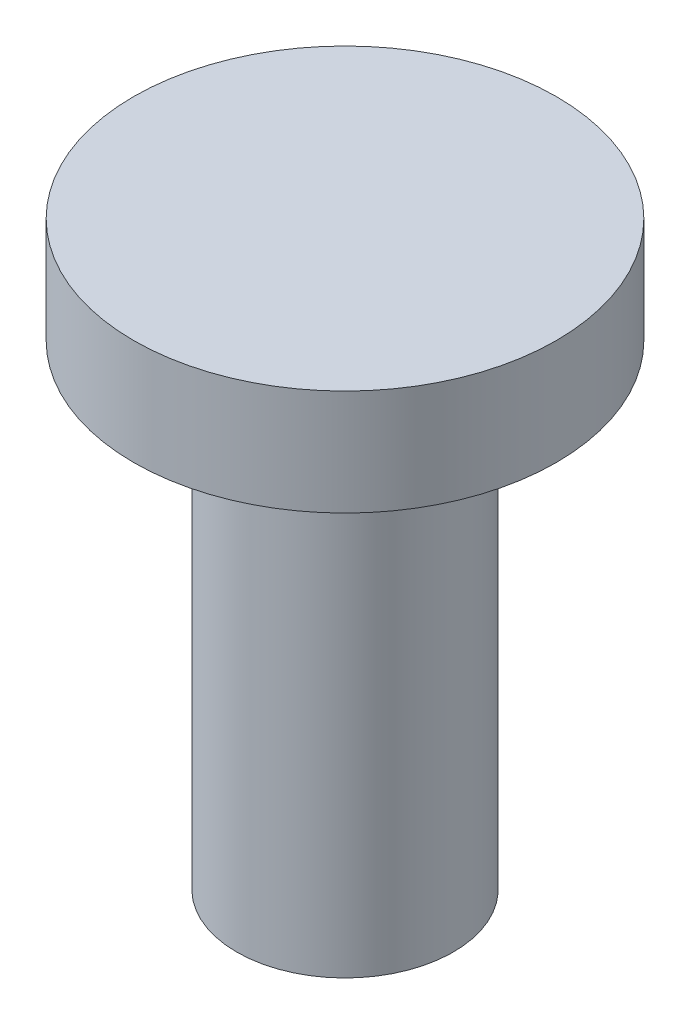
SolidWorks part; units mm, degrees
ref_plane "Front Plane" through (0, 0, 0) normal (0, 0, 1) x (1, 0, 0)
ref_plane "Top Plane" through (0, 0, 0) normal (0, 1, 0) x (1, 0, 0)
ref_plane "Right Plane" through (0, 0, 0) normal (1, 0, 0) x (0, 0, -1)
sketch "Sketch1" plane through (0, 0, 0) normal (0, 1, 0) x (1, 0, 0)
  circle A0 centre (0, 0) radius 1.025
  dimension "D1" = 2.05
extrude "Boss-Extrude1" add sketch "Sketch1" along normal blind 4.5
sketch "Sketch2" plane through (0, 4.5, 0) normal (0, 1, 0) x (1, 0, 0)
  circle A0 centre (0, 0) radius 2
extrude "Boss-Extrude2" add sketch "Sketch2" along normal blind 1
